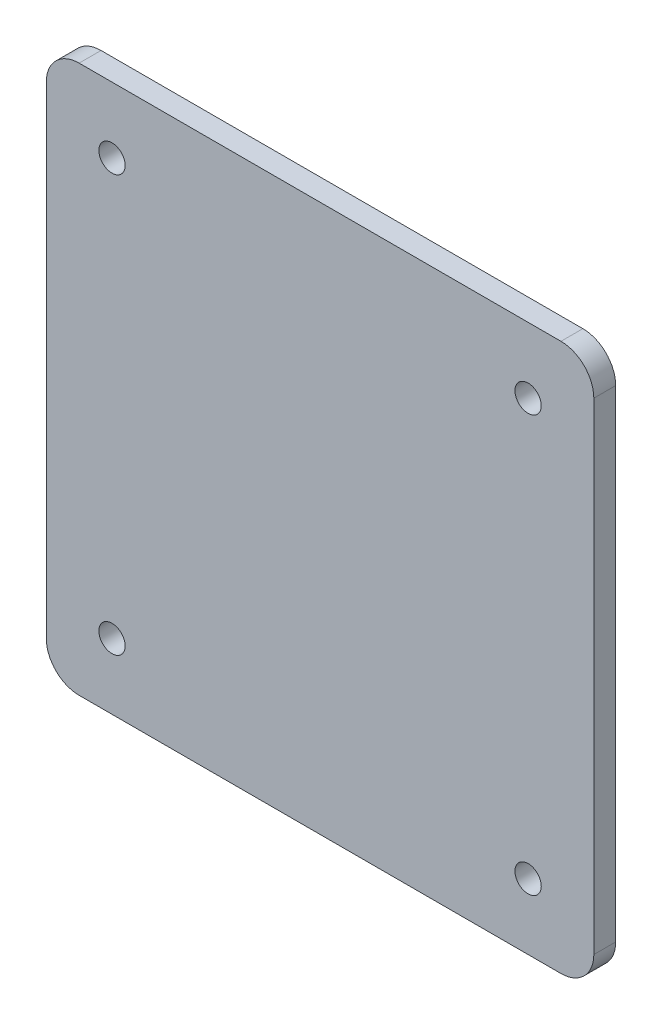
SolidWorks part; units mm, degrees
ref_plane "Front Plane" through (0, 0, 0) normal (0, 0, 1) x (1, 0, 0)
ref_plane "Top Plane" through (0, 0, 0) normal (0, 1, 0) x (1, 0, 0)
ref_plane "Right Plane" through (0, 0, 0) normal (1, 0, 0) x (0, 0, -1)
sketch "Sketch1" plane through (0, 0, 0) normal (0, 0, 1) x (1, 0, 0)
  line L1 (-95, 95) -> (95, 95) construction
  line L2 (-95, 95) -> (-95, -95) construction
  line L3 (-95, -95) -> (95, -95) construction
  line L4 (95, 95) -> (95, -95) construction
  line L5 (-95, 95) -> (95, -95) construction
  line L6 (-95, -95) -> (95, 95) construction
  line L7 (-110, 125) -> (110, 125)
  line L8 (-125, 110) -> (-125, -110)
  line L9 (-110, -125) -> (110, -125)
  line L10 (125, 110) -> (125, -110)
  line L11 (-125, 125) -> (125, -125) construction
  line L12 (-125, -125) -> (125, 125) construction
  circle A0 centre (-95, 95) radius 6
  circle A1 centre (-95, -95) radius 6
  circle A2 centre (95, -95) radius 6
  circle A3 centre (95, 95) radius 6
  arc A4 (110, 125) -> (125, 110) centre (110, 110) cw
  arc A5 (110, -125) -> (125, -110) centre (110, -110) ccw
  arc A6 (-125, -110) -> (-110, -125) centre (-110, -110) ccw
  arc A7 (-110, 125) -> (-125, 110) centre (-110, 110) ccw
  point P0 (0, 0)
  point P6 (0, 0)
  dimension "D3" = 12
  dimension "D4" = 15
  dimension "D1" = 250
  dimension "D2" = 190
extrude "Boss-Extrude1" add sketch "Sketch1" along normal blind 10
